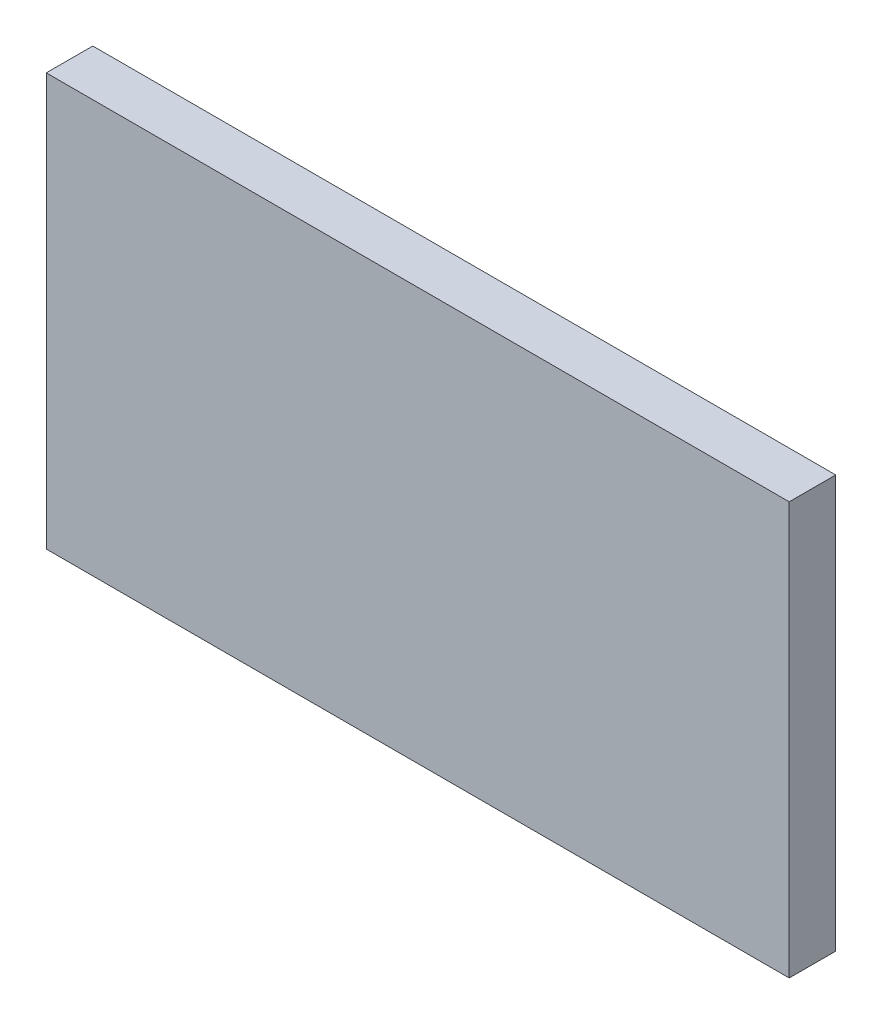
SolidWorks part; units mm, degrees
material "Alliage 1060"
ref_plane "Face" through (0, 0, 0) normal (0, 0, 1) x (1, 0, 0)
ref_plane "Dessus" through (0, 0, 0) normal (0, 1, 0) x (1, 0, 0)
ref_plane "Droite" through (0, 0, 0) normal (1, 0, 0) x (0, 0, -1)
sketch "Esquisse1" plane through (0, 0, 0) normal (0, 0, 1) x (1, 0, 0)
  line L1 (-11.98, 6.65) -> (11.98, 6.65)
  line L2 (-11.98, 6.65) -> (-11.98, -6.65)
  line L3 (-11.98, -6.65) -> (11.98, -6.65)
  line L4 (11.98, 6.65) -> (11.98, -6.65)
  line L5 (-11.98, 6.65) -> (11.98, -6.65) construction
  line L6 (-11.98, -6.65) -> (11.98, 6.65) construction
  point P0 (0, 0)
  dimension "D1" = 13.3
  dimension "D2" = 23.96
extrude "Boss.-Extru.1" add sketch "Esquisse1" along normal blind 1.5
